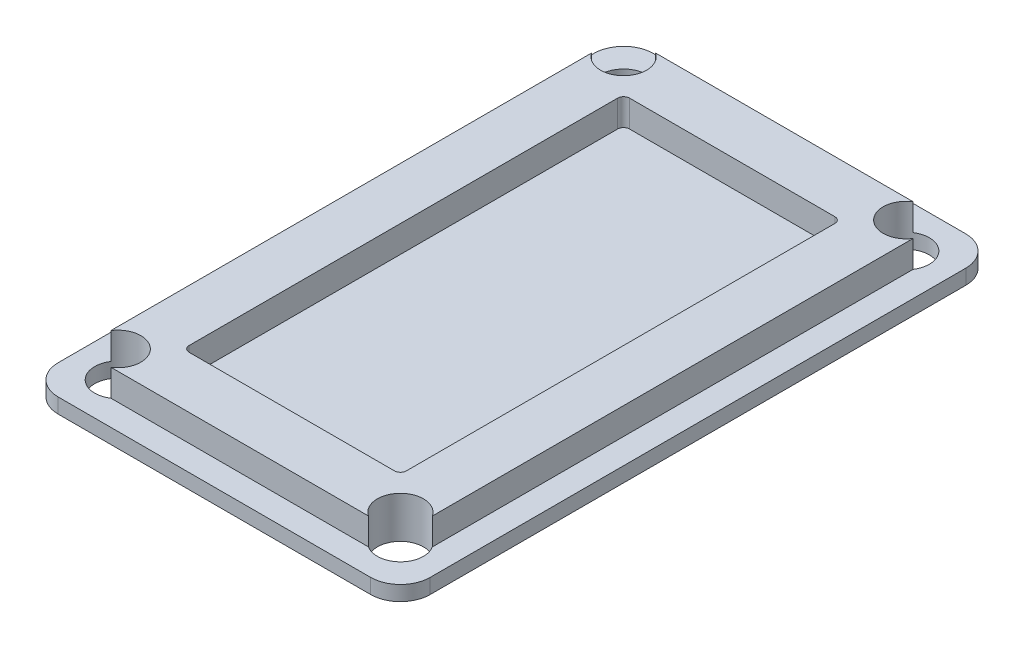
SolidWorks part; units mm, degrees
material "ABS"
ref_plane "Plan de face" through (0, 0, 0) normal (0, 0, 1) x (1, 0, 0)
ref_plane "Plan de dessus" through (0, 0, 0) normal (0, 1, 0) x (1, 0, 0)
ref_plane "Plan de droite" through (0, 0, 0) normal (1, 0, 0) x (0, 0, -1)
sketch "Esquisse1" plane through (0, 0, 0) normal (0, 1, 0) x (1, 0, 0)
  line L1 (-10.5, 20) -> (10.5, 20)
  line L2 (-12.5, 18) -> (-12.5, -18)
  line L3 (-10.5, -20) -> (10.5, -20)
  line L4 (12.5, 18) -> (12.5, -18)
  line L5 (-12.5, 20) -> (12.5, -20) construction
  line L6 (-12.5, -20) -> (12.5, 20) construction
  arc A0 (10.5, 20) -> (12.5, 18) centre (10.5, 18) cw
  arc A1 (10.5, -20) -> (12.5, -18) centre (10.5, -18) ccw
  arc A2 (-12.5, -18) -> (-10.5, -20) centre (-10.5, -18) ccw
  arc A3 (-10.5, 20) -> (-12.5, 18) centre (-10.5, 18) ccw
  point P0 (0, 0)
  dimension "D3" = 2
  dimension "D1" = 25
  dimension "D2" = 40
extrude "Base" add sketch "Esquisse1" along normal blind 1
sketch "Esquisse2" plane through (0, 1, 0) normal (0, 1, 0) x (1, 0, 0)
  line L5 (-6.9, 14.8) -> (6.9, 14.8)
  line L6 (-7.3, 14.4) -> (-7.3, -14.4)
  line L7 (-6.9, -14.8) -> (6.9, -14.8)
  line L8 (10.5, 18.3) -> (-10.5, 18.3)
  line L9 (-10.8, 18) -> (-10.8, -18)
  line L10 (-10.5, -18.3) -> (10.5, -18.3)
  line L11 (10.8, -18) -> (10.8, 18)
  line L12 (10.5, 18.3) -> (-10.5, 18.3)
  line L13 (-10.8, 18) -> (-10.8, -18)
  line L14 (-10.5, -18.3) -> (10.5, -18.3)
  line L15 (10.8, -18) -> (10.8, 18)
  line L16 (7.3, 14.4) -> (7.3, -14.4)
  line L17 (-7.3, 14.8) -> (7.3, -14.8) construction
  line L18 (-7.3, -14.8) -> (7.3, 14.8) construction
  arc A4 (-7.3, -14.4) -> (-6.9, -14.8) centre (-6.9, -14.4) ccw
  arc A5 (6.9, -14.8) -> (7.3, -14.4) centre (6.9, -14.4) ccw
  arc A6 (6.9, 14.8) -> (7.3, 14.4) centre (6.9, 14.4) cw
  arc A7 (-6.9, 14.8) -> (-7.3, 14.4) centre (-6.9, 14.4) ccw
  arc A8 (10.8, 18) -> (10.5, 18.3) centre (10.5, 18) ccw
  arc A9 (-10.5, 18.3) -> (-10.8, 18) centre (-10.5, 18) ccw
  arc A10 (-10.8, -18) -> (-10.5, -18.3) centre (-10.5, -18) ccw
  arc A11 (10.5, -18.3) -> (10.8, -18) centre (10.5, -18) ccw
  arc A12 (10.8, 18) -> (10.5, 18.3) centre (10.5, 18) ccw
  arc A13 (-10.5, 18.3) -> (-10.8, 18) centre (-10.5, 18) ccw
  arc A14 (-10.8, -18) -> (-10.5, -18.3) centre (-10.5, -18) ccw
  arc A15 (10.5, -18.3) -> (10.8, -18) centre (10.5, -18) ccw
  point P0 (0, 0)
  dimension "D4" = 0.4
  dimension "D2" = 3.5
  dimension "D3" = 3.5
  dimension "D1" = 1.7
extrude "Intérieur" add sketch "Esquisse2" along normal blind 1.8
sketch "Esquisse4" plane through (0, 0, 0) normal (0, -1, 0) x (1, 0, 0)
  line L1 (-10.5, 20) -> (10.5, 20) construction
  line L2 (-6.5, 14) -> (-12.5, 14) construction
  line L3 (-6.5, 14) -> (-6.5, 20) construction
  line L4 (-6.5, 20) -> (-12.5, 20) construction
  line L5 (-12.5, 14) -> (-12.5, 20) construction
  line L6 (-12.5, -18) -> (-12.5, 18) construction
  line L7 (0, -55) -> (0, 55) construction
  line L8 (55, 0) -> (-55, 0) construction
  circle A0 centre (-9.5, 17) radius 1.55
  circle A1 centre (9.5, 17) radius 1.55
  circle A2 centre (9.5, -17) radius 1.55
  circle A3 centre (-9.5, -17) radius 1.55
  point P13 (-9.5, 20)
  point P15 (-6.5, 17)
  dimension "D1" = 3.1
  dimension "D2" = 6
  dimension "D3" = 6
extrude "Passage_Vis" cut sketch "Esquisse4" against normal up to next
sketch "Esquisse5" plane through (0, 2.8, 0) normal (0, 1, 0) x (1, 0, 0)
  line L0 (-10.8, 16.1559) -> (-10.8, -16.1559) construction
  line L1 (-13.8, 21.3) -> (13.8, 21.3)
  line L2 (-13.8, 21.3) -> (-13.8, -21.3)
  line L3 (-13.8, -21.3) -> (13.8, -21.3)
  line L4 (13.8, 21.3) -> (13.8, -21.3)
  line L5 (-9.2, 18.3) -> (9.2, 18.3)
  line L6 (-10.8, 16.7) -> (-10.8, -16.7)
  line L7 (-9.2, -18.3) -> (9.2, -18.3)
  line L8 (10.8, 16.7) -> (10.8, -16.7)
  line L9 (8.6559, 18.3) -> (-8.6559, 18.3) construction
  line L12 (-8.6559, -18.3) -> (8.6559, -18.3) construction
  line L13 (10.8, -16.1559) -> (10.8, 16.1559) construction
  arc A0 (-10.8, -16.7) -> (-9.2, -18.3) centre (-9.2, -16.7) ccw
  arc A1 (9.2, -18.3) -> (10.8, -16.7) centre (9.2, -16.7) ccw
  arc A2 (9.2, 18.3) -> (10.8, 16.7) centre (9.2, 16.7) cw
  arc A3 (-9.2, 18.3) -> (-10.8, 16.7) centre (-9.2, 16.7) ccw
  point P24 (17.0337, -22.0149)
  dimension "D1" = 1.6
  dimension "D2" = 3
  dimension "D3" = 3
  dimension "D4" = 3
  dimension "D5" = 3
extrude "Cleaning" cut sketch "Esquisse5" against normal up to surface (1.8 mm away) up to face at (0, 1, 0)
